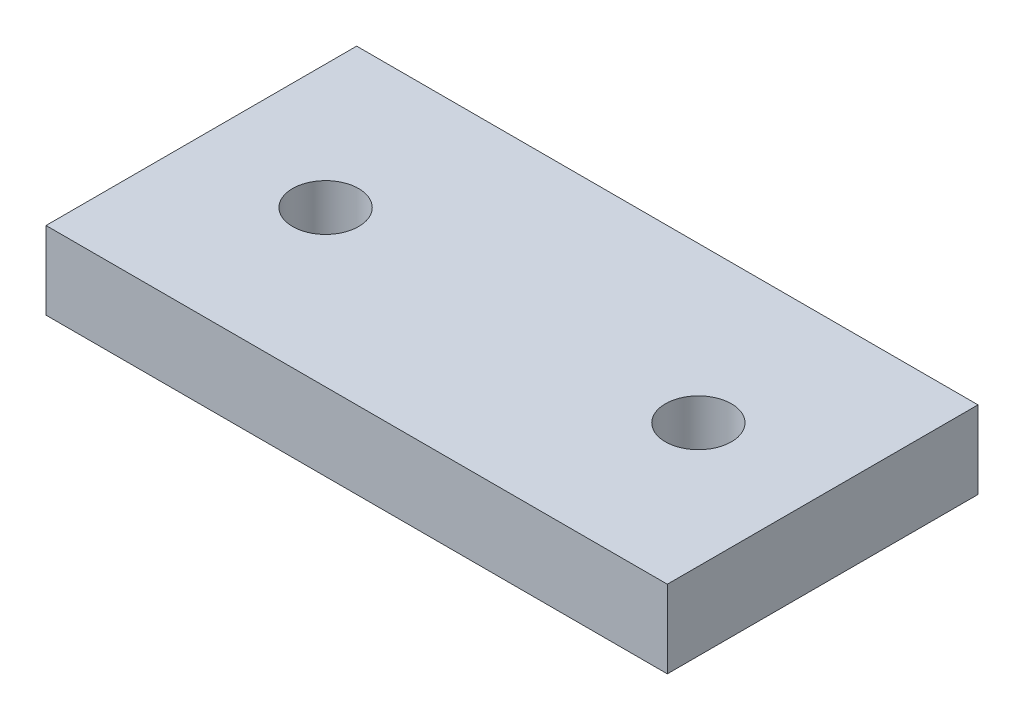
SolidWorks part; units mm, degrees
ref_plane "Front Plane" through (0, 0, 0) normal (0, 0, 1) x (1, 0, 0)
ref_plane "Top Plane" through (0, 0, 0) normal (0, 1, 0) x (1, 0, 0)
ref_plane "Right Plane" through (0, 0, 0) normal (1, 0, 0) x (0, 0, -1)
sketch "Sketch1" plane through (0, 0, 0) normal (0, 1, 0) x (1, 0, 0)
  line L0 (0, 10) -> (0, -10) construction
  line L1 (-20, -10) -> (20, -10)
  line L2 (-20, -10) -> (-20, 10)
  line L3 (-20, 10) -> (20, 10)
  line L4 (20, -10) -> (20, 10)
  line L5 (-20, -10) -> (20, 10) construction
  line L6 (-20, 10) -> (20, -10) construction
  circle A0 centre (-12, 0) radius 2.125
  circle A1 centre (12, 0) radius 2.125
  point P0 (0, 0)
  dimension "D3" = 4.25
  dimension "D1" = 20
  dimension "D2" = 40
  dimension "D4" = 8
extrude "Boss-Extrude1" add sketch "Sketch1" along normal blind 5
